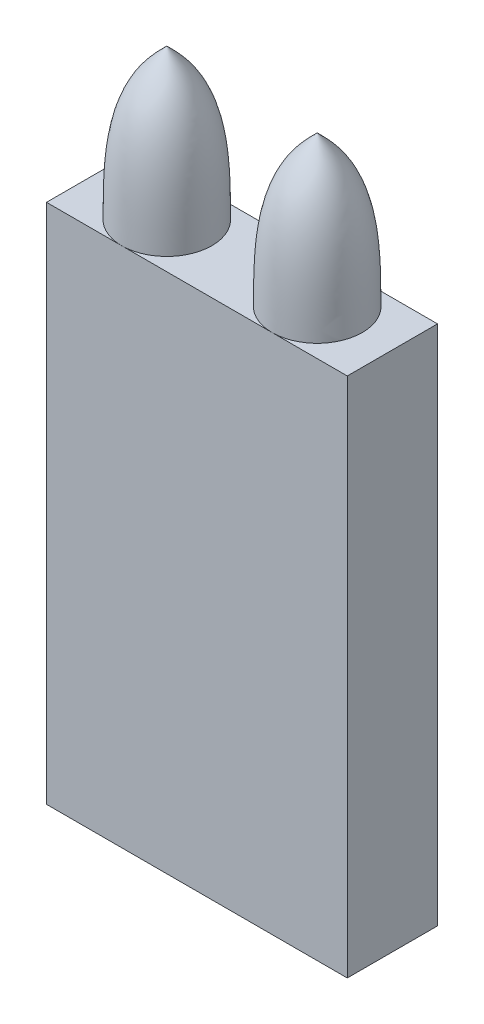
SolidWorks part; units mm, degrees
ref_plane "Plan de face" through (0, 0, 0) normal (0, 0, 1) x (1, 0, 0)
ref_plane "Plan de dessus" through (0, 0, 0) normal (0, 1, 0) x (1, 0, 0)
ref_plane "Plan de droite" through (0, 0, 0) normal (1, 0, 0) x (0, 0, -1)
sketch "Esquisse1" plane through (0, 0, 0) normal (0, 0, 1) x (1, 0, 0)
  line L0 (0, 0) -> (0, -35) construction
  line L1 (2, -0.3328) -> (5, -0.3328)
  line L2 (5, 9.6672) -> (5, -0.3328)
  line L3 (-5, -0.3328) -> (-5, 9.6672) construction
  line L4 (-2, -0.3328) -> (-5, -0.3328)
  spline S0 degree 3 poles (2, -0.3328) (2.0103, 2.8567) (2.0227, 6.6953) (4.5694, 9.2374) (5, 9.6672) knots 0 0 0 0 0.830907 1 1 1 1
  spline S1 degree 3 poles (-2, -0.3328) (-2.0103, 2.8567) (-2.0227, 6.6953) (-4.5694, 9.2374) (-5, 9.6672) knots 0 0 0 0 0.830907 1 1 1 1
  dimension "D3" = 35
  dimension "D4" = 10
revolve "Révolution1" add sketch "Esquisse1" angle 360 about L2
sketch "Esquisse2" plane through (0, 0, 0) normal (0, 0, 1) x (1, 0, 0)
  line L0 (0, 0) -> (0, -35) construction
  line L1 (-5, -0.3328) -> (-5, 9.6672)
  line L3 (-5, -0.3328) -> (-5, 9.6672) construction
  line L4 (-2, -0.3328) -> (-5, -0.3328)
  spline S1 degree 3 poles (-2, -0.3328) (-2.0103, 2.8567) (-2.0227, 6.6953) (-4.5694, 9.2374) (-5, 9.6672) knots 0 0 0 0 0.830907 1 1 1 1
  dimension "D3" = 35
revolve "Révolution2" add sketch "Esquisse2" angle 360 about L3
sketch "Esquisse3" plane through (0, 0, 0) normal (0, 0, 1) x (1, 0, 0)
  line L0 (0, 0) -> (0, -35) construction
  line L2 (-10, -0.3328) -> (10, -0.3328)
  line L3 (-5, -0.3328) -> (-5, 9.6672) construction
  line L4 (-2, -0.3328) -> (-5, -0.3328)
  line L5 (-10, -0.3328) -> (-10, -35)
  line L6 (-10, -35) -> (10, -35)
  line L7 (10, -0.3328) -> (10, -35)
  spline S1 degree 3 poles (-2, -0.3328) (-2.0103, 2.8567) (-2.0227, 6.6953) (-4.5694, 9.2374) (-5, 9.6672) knots 0 0 0 0 0.830907 1 1 1 1
  dimension "D1" = 20
  dimension "D2" = 10
  dimension "D3" = 35
extrude "Extrusion1" add sketch "Esquisse3" along normal blind 3
sketch "Esquisse4" plane through (0, 0, 0) normal (0, 0, -1) x (-1, 0, 0)
  line L1 (10, -0.3328) -> (-10, -0.3328)
  line L2 (10, -0.3328) -> (10, -35)
  line L3 (10, -35) -> (-10, -35)
  line L4 (-10, -0.3328) -> (-10, -35)
extrude "Extrusion2" add sketch "Esquisse4" along normal blind 3
sketch "Esquisse5" plane through (0, 0, -3) normal (0, 0, -1) x (-1, 0, 0)
  line L0 (2.6897, -3.903) -> (2.6897, -31.4946) construction
  text T0 "Capture" font "Century Gothic" height 3.5
extrude "Enlèv. mat.-Extru.1" cut sketch "Esquisse5" against normal blind 2
